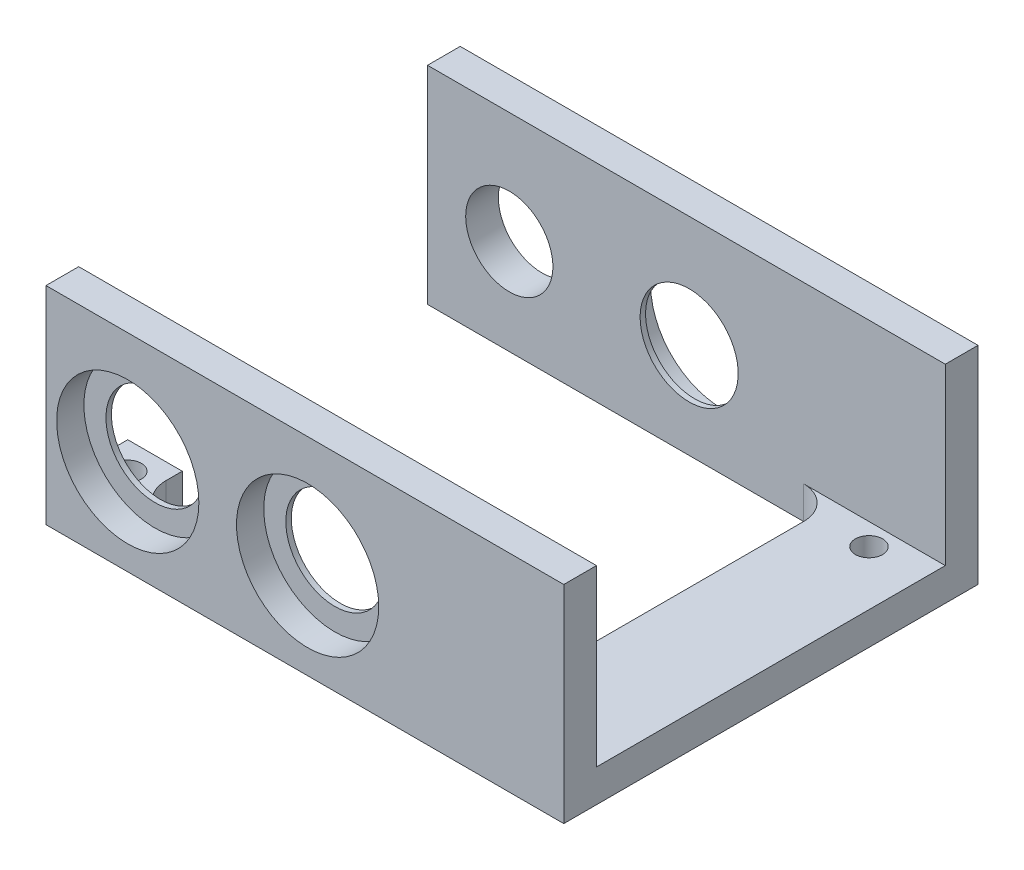
SolidWorks part; units mm, degrees
material "6061 Alloy"
ref_plane "Front Plane" through (0, 0, 0) normal (0, 0, 1) x (1, 0, 0)
ref_plane "Top Plane" through (0, 0, 0) normal (0, 1, 0) x (1, 0, 0)
ref_plane "Right Plane" through (0, 0, 0) normal (1, 0, 0) x (0, 0, -1)
sketch "Sketch1" plane through (0, 0, 0) normal (0, 0, 1) x (1, 0, 0)
  line L1 (-39.5619, 28.487) -> (55.4381, 28.487)
  line L2 (-39.5619, 28.487) -> (-39.5619, -9.513)
  line L3 (-39.5619, -9.513) -> (55.4381, -9.513)
  line L4 (55.4381, 28.487) -> (55.4381, -9.513)
  dimension "D1" = 95
  dimension "D2" = 38
extrude "Boss-Extrude1" add sketch "Sketch1" along normal blind 6
ref_plane "Plane1" through (0, 0, 70) normal (0, 0, 1) x (1, 0, 0)
sketch "Sketch2" plane through (0, 0, 70) normal (0, 0, 1) x (1, 0, 0)
  line L1 (-39.5619, 28.487) -> (55.4381, 28.487)
  line L2 (-39.5619, 28.487) -> (-39.5619, -9.513)
  line L3 (-39.5619, -9.513) -> (55.4381, -9.513)
  line L4 (55.4381, 28.487) -> (55.4381, -9.513)
extrude "Boss-Extrude2" add sketch "Sketch2" along normal blind 6 separate body
ref_plane "Plane3" through (0, -9.513, 0) normal (0, -1, 0) x (-1, 0, 0)
sketch "Sketch11" plane through (0, -9.513, 0) normal (0, -1, 0) x (-1, 0, 0)
  line L0 (39.5619, -70) -> (-55.4381, -70) construction
  line L1 (-55.4381, -6) -> (-35.437, -6)
  line L2 (-55.4381, -6) -> (-55.4381, -70)
  line L3 (-55.4381, -70) -> (-35.437, -70)
  line L4 (-35.437, -6) -> (-35.437, -70)
extrude "Boss-Extrude5" add sketch "Sketch11" against normal blind 6
sketch "Sketch13" plane through (0, -9.513, 0) normal (0, -1, 0) x (-1, 0, 0)
  line L1 (39.5619, -70) -> (29.5619, -70)
  line L2 (39.5619, -70) -> (39.5619, -61)
  line L3 (39.5619, -61) -> (29.5619, -61)
  line L4 (29.5619, -70) -> (29.5619, -61)
  dimension "D1" = 10
  dimension "D2" = 9
extrude "Boss-Extrude7" add sketch "Sketch13" against normal blind 6
sketch "Sketch14" plane through (0, 0, 76) normal (0, 0, 1) x (1, 0, 0)
  line L0 (-39.5619, -9.513) -> (-24.5619, -9.513) construction
  line L1 (-39.5619, -9.513) -> (55.4381, -9.513) construction
  line L2 (-24.5619, -9.513) -> (-24.5619, 7.987) construction
  line L3 (-24.5619, 7.987) -> (8.4381, 7.987) construction
sketch "Sketch15" plane through (0, 0, 0) normal (0, 0, -1) x (-1, 0, 0)
  line L0 (39.5619, -9.513) -> (24.5619, -9.513) construction
  line L1 (39.5619, -9.513) -> (-55.4381, -9.513) construction
  line L2 (24.5619, -9.513) -> (24.5619, 7.987) construction
  line L3 (24.5619, 7.987) -> (-8.4381, 7.987) construction
sketch "Sketch16" plane through (0, 0, 76) normal (0, 0, 1) x (1, 0, 0)
  circle A0 centre (-24.5619, 7.987) radius 9
  circle A1 centre (8.4381, 7.987) radius 9
extrude "Cut-Extrude2" cut sketch "Sketch16" against normal blind 6
sketch "Sketch20" plane through (0, 0, 76) normal (0, 0, 1) x (1, 0, 0)
  circle A0 centre (-24.5619, 7.987) radius 13.05
  circle A1 centre (8.4381, 7.987) radius 13.05
extrude "Cut-Extrude3" cut sketch "Sketch20" against normal blind 5
sketch "Sketch21" plane through (0, 0, 0) normal (0, 0, -1) x (-1, 0, 0)
  circle A0 centre (24.5619, 7.987) radius 8
  circle A1 centre (-8.4381, 7.987) radius 9
extrude "Cut-Extrude4" cut sketch "Sketch21" against normal blind 6
sketch "Sketch22" plane through (0, 0, 0) normal (0, 0, -1) x (-1, 0, 0)
  circle A0 centre (-8.4381, 7.987) radius 13.05
extrude "Cut-Extrude5" cut sketch "Sketch22" against normal blind 5
sketch "Sketch23" plane through (0, -3.513, 0) normal (0, 1, 0) x (1, 0, 0)
  line L0 (-39.5619, -61) -> (-34.5619, -61) construction
  line L1 (-39.5619, -61) -> (-29.5619, -61) construction
  line L2 (-34.5619, -61) -> (-34.5619, -66) construction
sketch "Sketch24" plane through (0, -3.513, 0) normal (0, 1, 0) x (1, 0, 0)
  line L0 (55.4381, -70) -> (45.4375, -70) construction
  line L1 (55.4381, -70) -> (35.437, -70) construction
  line L2 (45.4375, -70) -> (45.4375, -66) construction
  line L3 (45.4375, -66) -> (45.4375, -10) construction
sketch "Sketch25" plane through (0, -3.513, 0) normal (0, 1, 0) x (1, 0, 0)
  circle A0 centre (45.4375, -10) radius 2.5
  circle A1 centre (45.4375, -66) radius 2.5
  circle A2 centre (-34.5619, -66) radius 2.5
extrude "Cut-Extrude6" cut sketch "Sketch25" against normal blind 6
fillet "Fillet2" radius 6 3 edges at (35.437, -6.513, 6) (35.437, -6.513, 70) (-29.5619, -6.513, 70)
